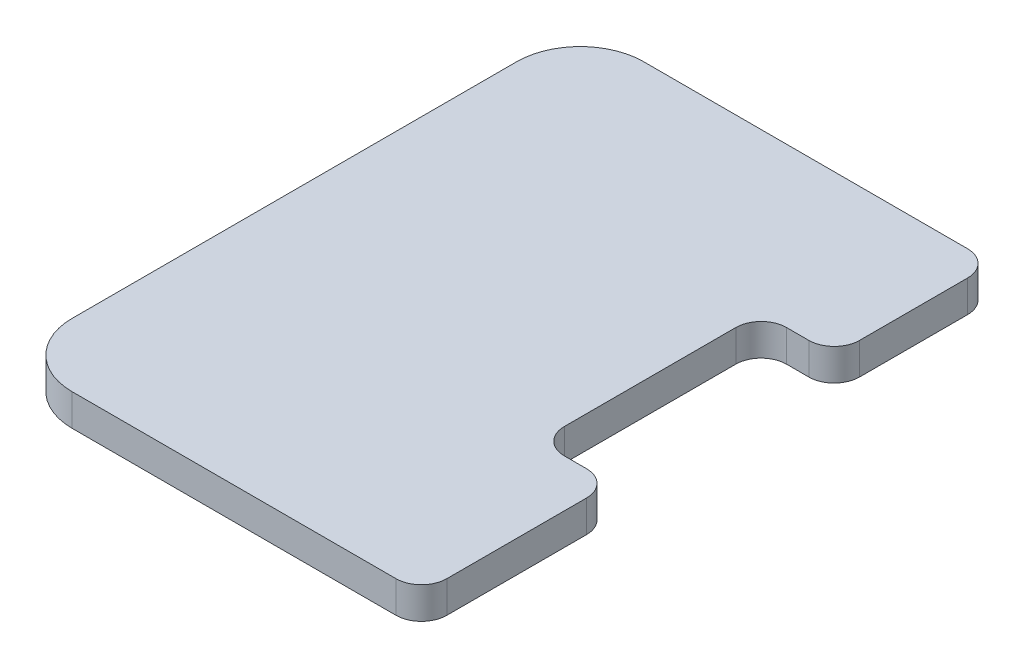
SolidWorks part; units mm, degrees
ref_plane "Front Plane" through (0, 0, 0) normal (0, 0, 1) x (1, 0, 0)
ref_plane "Top Plane" through (0, 0, 0) normal (0, 1, 0) x (1, 0, 0)
ref_plane "Right Plane" through (0, 0, 0) normal (1, 0, 0) x (0, 0, -1)
sketch "Sketch1" plane through (0, 0, 0) normal (0, 1, 0) x (1, 0, 0)
  line L1 (-20.6375, -28.575) -> (20.6375, -28.575)
  line L2 (-20.6375, -28.575) -> (-20.6375, 28.575)
  line L3 (-20.6375, 28.575) -> (20.6375, 28.575)
  line L4 (20.6375, -28.575) -> (20.6375, 28.575)
  line L5 (-20.6375, -28.575) -> (20.6375, 28.575) construction
  line L6 (-20.6375, 28.575) -> (20.6375, -28.575) construction
  point P0 (0, 0)
  dimension "D1" = 57.15
  dimension "D2" = 41.275
extrude "Boss-Extrude1" add sketch "Sketch1" along normal blind 3.175
sketch "Sketch2" plane through (0, 3.175, 0) normal (0, 1, 0) x (1, 0, 0)
  line L0 (20.6375, -9.525) -> (13.335, -9.525)
  line L1 (20.6375, -28.575) -> (20.6375, 28.575) construction
  line L2 (13.335, -9.525) -> (13.335, 12.7)
  line L3 (13.335, 12.7) -> (20.6375, 12.7)
  line L4 (20.6375, 28.575) -> (-20.6375, 28.575) construction
  line L5 (-20.6375, -28.575) -> (20.6375, -28.575) construction
  line L6 (20.6375, -9.525) -> (20.6375, 12.7)
  dimension "D1" = 15.875
  dimension "D2" = 19.05
  dimension "D3" = 7.3025
extrude "Cut-Extrude2" cut sketch "Sketch2" against normal through all
fillet "Fillet1" radius 2.54 6 edges at (20.6375, 1.5875, 28.575) (20.6375, 1.5875, -28.575) (20.6375, 1.5875, 9.525) (13.335, 1.5875, 9.525) (20.6375, 1.5875, -12.7) (13.335, 1.5875, -12.7)
fillet "Fillet2" radius 6.35 2 edges at (-20.6375, 1.5875, 28.575) (-20.6375, 1.5875, -28.575)
